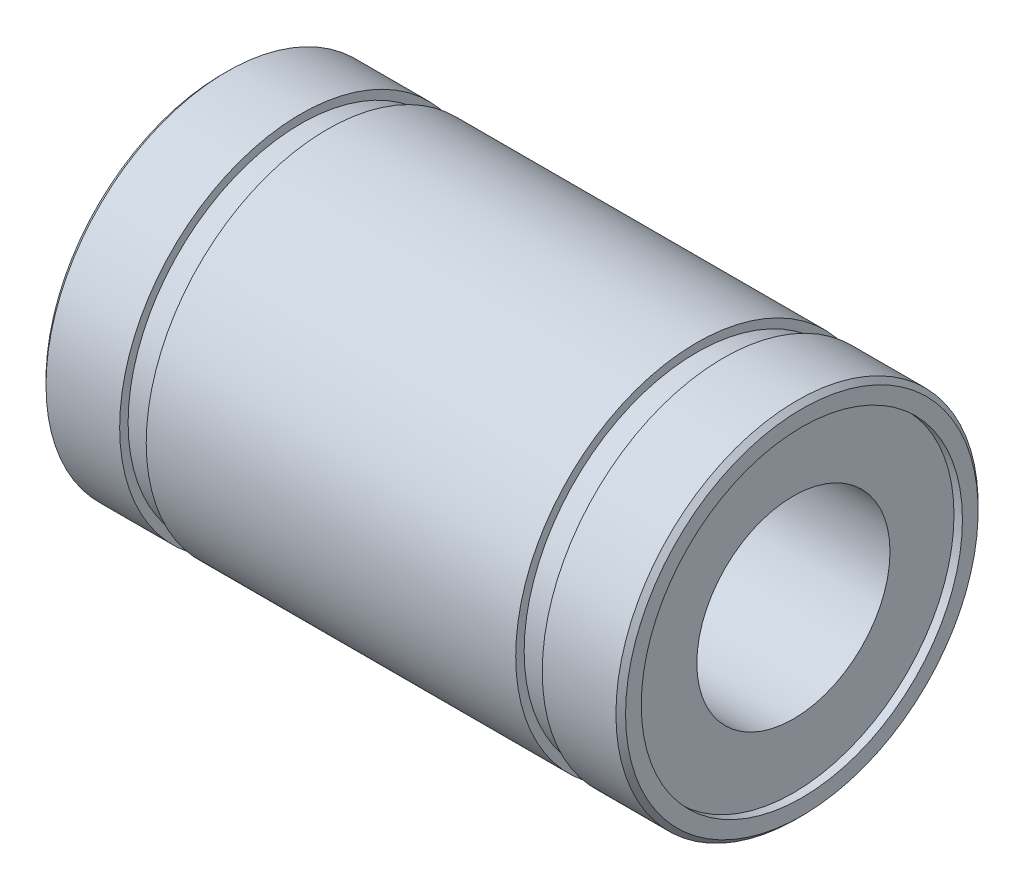
SolidWorks part; units mm, degrees
ref_plane "Front Plane" through (0, 0, 0) normal (0, 0, 1) x (1, 0, 0)
ref_plane "Top Plane" through (0, 0, 0) normal (0, 1, 0) x (1, 0, 0)
ref_plane "Right Plane" through (0, 0, 0) normal (1, 0, 0) x (0, 0, -1)
sketch "Sketch1" plane through (0, 0, 0) normal (0, 0, 1) x (1, 0, 0)
  line L0 (0, 0) -> (112.5581, 0) construction
  line L1 (0.35, 4) -> (0.35, 6.65)
  line L2 (0.35, 6.65) -> (0, 6.65)
  line L3 (0, 6.65) -> (0, 7.5)
  line L4 (0, 7.5) -> (3.25, 7.5)
  line L5 (3.25, 7.5) -> (3.25, 7.15)
  line L6 (3.25, 7.15) -> (4.35, 7.15)
  line L7 (4.35, 7.15) -> (4.35, 7.5)
  line L8 (4.35, 7.5) -> (19.65, 7.5)
  line L9 (19.65, 7.5) -> (19.65, 7.15)
  line L10 (19.65, 7.15) -> (20.75, 7.15)
  line L11 (20.75, 7.15) -> (20.75, 7.5)
  line L12 (20.75, 7.5) -> (24, 7.5)
  line L13 (24, 7.5) -> (24, 6.65)
  line L14 (24, 6.65) -> (23.65, 6.65)
  line L15 (23.65, 6.65) -> (23.65, 4)
  line L16 (23.65, 4) -> (0.35, 4)
  dimension "D1" = 8
  dimension "D2" = 15
  dimension "D3" = 1.1
  dimension "D4" = 17.5
  dimension "D5" = 24
  dimension "D6" = 14.3
  dimension "D7" = 0.5
revolve "Revolve1" add sketch "Sketch1" angle 360 about L0
chamfer "Chamfer1" distance 0.2 angle 45 2 edges at (24, 0, 7.5) (0, 0, 7.5)
